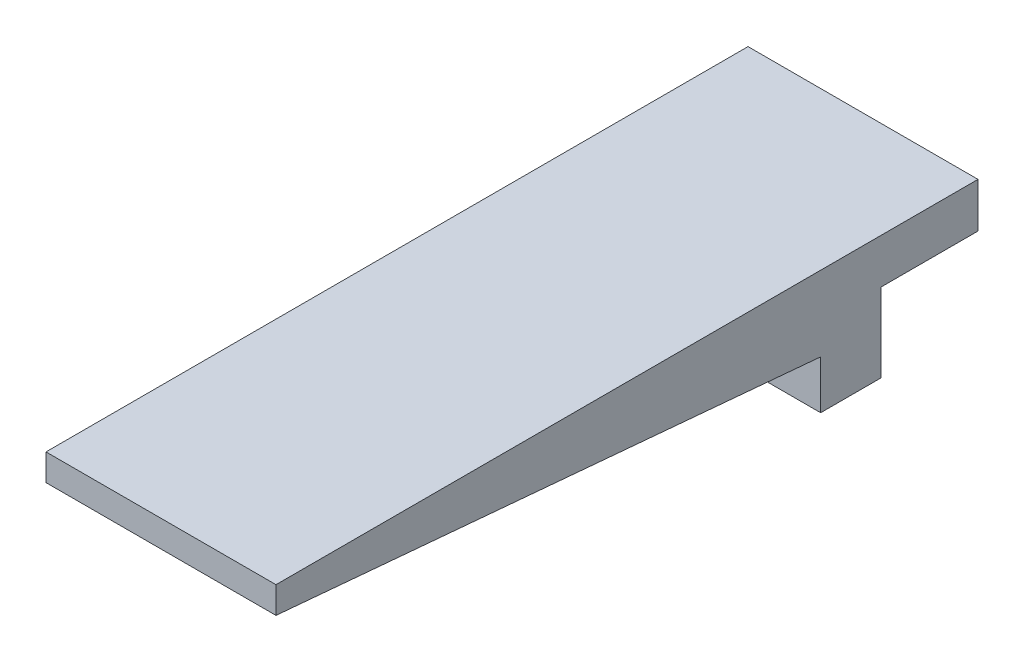
SolidWorks part; units mm, degrees
ref_plane "Front Plane" through (0, 0, 0) normal (0, 0, 1) x (1, 0, 0)
ref_plane "Top Plane" through (0, 0, 0) normal (0, 1, 0) x (1, 0, 0)
ref_plane "Right Plane" through (0, 0, 0) normal (1, 0, 0) x (0, 0, -1)
sketch "Sketch1" plane through (0, 0, 0) normal (0, 0, 1) x (1, 0, 0)
  line L1 (-9.5, 3.25) -> (9.5, 3.25)
  line L2 (-9.5, 3.25) -> (-9.5, -3.25)
  line L3 (-9.5, -3.25) -> (9.5, -3.25)
  line L4 (9.5, 3.25) -> (9.5, -3.25)
  line L5 (0, -3.25) -> (0, 3.25) construction
  line L6 (-9.5, 0) -> (9.5, 0) construction
  point P0 (0, 0)
  dimension "D1" = 19
  dimension "D2" = 6.5
extrude "Boss-Extrude1" add sketch "Sketch1" along normal blind 50
sketch "Sketch2" plane through (0, 3.25, 0) normal (0, 1, 0) x (1, 0, 0)
  line L0 (-9.5, -50) -> (-9.5, 0) construction
  line L1 (9.5, -50) -> (-9.5, -50)
  line L2 (9.5, -50) -> (9.5, 8)
  line L3 (9.5, 8) -> (-9.5, 8)
  line L4 (-9.5, -50) -> (-9.5, 8)
  dimension "D1" = 58
extrude "Boss-Extrude2" add sketch "Sketch2" along normal blind 3.7
sketch "Sketch3" plane through (-9.5, 0, 0) normal (-1, 0, 0) x (0, 0, 1)
  line L1 (50, -3.25) -> (0, -3.25) construction
  line L2 (50, 6.95) -> (50, -3.25) construction
  line L3 (50, 4.75) -> (50, -3.25)
  line L4 (50, -3.25) -> (5, -3.25)
  line L5 (50, 4.75) -> (5, 0.75)
  line L6 (5, 0.75) -> (5, -3.25)
  dimension "D1" = 45
  dimension "D2" = 8
  dimension "D3" = 4
extrude "Cut-Extrude1" cut sketch "Sketch3" against normal through all
